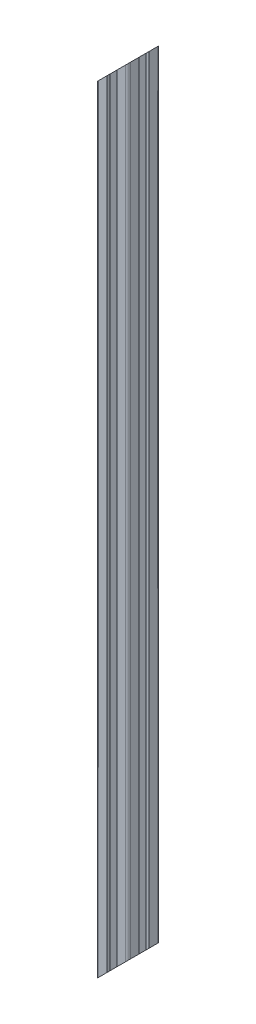
SolidWorks part; units mm, degrees
ref_plane "前视基准面" through (0, 0, 0) normal (0, 0, 1) x (1, 0, 0)
ref_plane "上视基准面" through (0, 0, 0) normal (0, 1, 0) x (1, 0, 0)
ref_plane "右视基准面" through (0, 0, 0) normal (1, 0, 0) x (0, 0, -1)
sketch "草图1" plane through (0, 0, 0) normal (0, 1, 0) x (1, 0, 0)
  line L0 (-12.6113, -4.7896) -> (-10.8113, -4.7896)
  line L1 (-11.1113, 8.3104) -> (5.8887, 8.3104)
  line L2 (-12.6113, 6.8104) -> (-12.6113, -10.1896)
  line L3 (-11.1113, -11.6896) -> (5.8887, -11.6896)
  line L4 (7.3887, 6.8104) -> (7.3887, -10.1896)
  line L5 (-12.6113, 8.3104) -> (7.3887, -11.6896) construction
  line L6 (-12.6113, -11.6896) -> (7.3887, 8.3104) construction
  line L7 (-5.6654, 1.4104) -> (0.4429, 1.4104)
  line L8 (-5.6654, 1.4104) -> (-5.6654, -4.7896)
  line L9 (-5.6654, -4.7896) -> (0.4429, -4.7896)
  line L10 (0.4429, 1.4104) -> (0.4429, -4.7896)
  line L11 (-5.6654, 1.4104) -> (0.4429, -4.7896) construction
  line L12 (-5.6654, -4.7896) -> (0.4429, 1.4104) construction
  line L13 (-10.8113, -4.7896) -> (-10.8113, -7.1896)
  line L14 (-10.8113, -7.1896) -> (-9.0083, -7.1896)
  line L15 (-9.0083, -7.1896) -> (-5.6654, -3.8467)
  line L16 (-8.1113, 4.7074) -> (-4.7683, 1.3645)
  line L17 (-8.1113, 6.5104) -> (-8.1113, 4.7074)
  line L18 (-5.7113, 6.5104) -> (-8.1113, 6.5104)
  line L19 (-5.7113, 8.3104) -> (-5.7113, 6.5104)
  line L20 (3.7858, 3.8104) -> (0.4429, 0.4674)
  line L21 (5.5887, 3.8104) -> (3.7858, 3.8104)
  line L22 (5.5887, 1.4104) -> (5.5887, 3.8104)
  line L23 (7.3887, 1.4104) -> (5.5887, 1.4104)
  line L24 (2.8887, -8.0867) -> (-0.4542, -4.7438)
  line L25 (2.8887, -9.8896) -> (2.8887, -8.0867)
  line L26 (0.4887, -9.8896) -> (2.8887, -9.8896)
  line L27 (0.4887, -11.6896) -> (0.4887, -9.8896)
  line L28 (-5.7113, -11.6896) -> (-5.7113, -9.8896)
  line L29 (-5.7113, -9.8896) -> (-8.1113, -9.8896)
  line L30 (-8.1113, -9.8896) -> (-8.1113, -8.0867)
  line L31 (-8.1113, -8.0867) -> (-4.7683, -4.7438)
  line L32 (-10.8113, 3.8104) -> (-9.0083, 3.8104)
  line L33 (-9.0083, 3.8104) -> (-5.6654, 0.4674)
  line L34 (-10.8113, 1.4104) -> (-10.8113, 3.8104)
  line L35 (-12.6113, 1.4104) -> (-10.8113, 1.4104)
  line L36 (2.8887, 6.5104) -> (2.8887, 4.7074)
  line L37 (2.8887, 4.7074) -> (-0.4542, 1.3645)
  line L38 (0.4887, 6.5104) -> (2.8887, 6.5104)
  line L39 (0.4887, 8.3104) -> (0.4887, 6.5104)
  line L40 (5.5887, -7.1896) -> (3.7858, -7.1896)
  line L41 (3.7858, -7.1896) -> (0.4429, -3.8467)
  line L42 (5.5887, -4.7896) -> (5.5887, -7.1896)
  line L43 (7.3887, -4.7896) -> (5.5887, -4.7896)
  circle A0 centre (-2.6113, -1.6896) radius 2.5
  arc A1 (-12.6113, 6.8104) -> (-11.1113, 8.3104) centre (-11.1113, 6.8104) cw
  arc A2 (-12.6113, -10.1896) -> (-11.1113, -11.6896) centre (-11.1113, -10.1896) ccw
  arc A3 (5.8887, 8.3104) -> (7.3887, 6.8104) centre (5.8887, 6.8104) cw
  arc A4 (7.3887, -10.1896) -> (5.8887, -11.6896) centre (5.8887, -10.1896) cw
  point P0 (-2.6113, -1.6896)
  point P19 (-2.6113, -1.6896)
  point P25 (-2.6113, -1.6896)
  point P31 (-2.6113, -1.6896)
  point P37 (-2.6113, -1.6896)
  point P59 (-2.6113, -1.6896)
extrude "凸台-拉伸1" add sketch "草图1" along normal blind 506.79
sketch "草图2" plane through (0, 0, -8.3104) normal (0, 0, -1) x (-1, 0, 0)
  line L0 (-7.3887, 506.79) -> (12.6113, 486.79)
  line L1 (12.6113, 506.79) -> (12.6113, 0) construction
  line L2 (12.6113, 0) -> (-7.3887, 20)
  line L3 (-7.3887, 506.79) -> (-7.3887, 0) construction
  line L4 (-7.3887, 20) -> (-7.3887, 0)
  line L5 (-7.3887, 0) -> (12.6113, 0)
  line L6 (-7.3887, 506.79) -> (12.6113, 506.79)
  line L7 (12.6113, 506.79) -> (12.6113, 486.79)
  dimension "D1" = 45
  dimension "D2" = 45
extrude "切除-拉伸1" cut sketch "草图2" against normal through all
